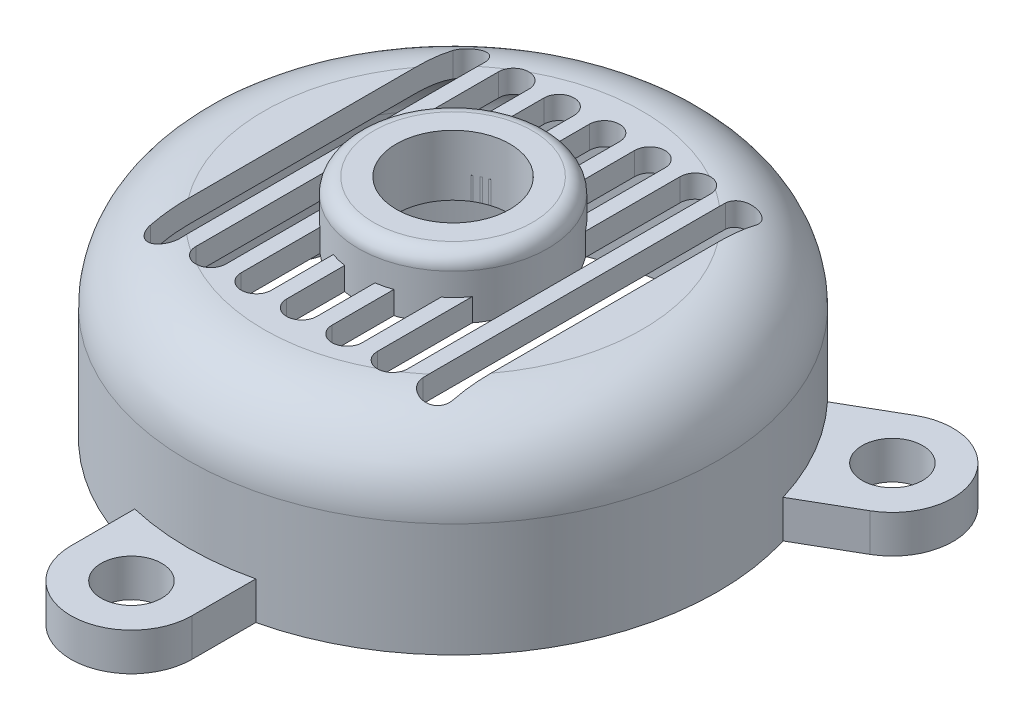
SolidWorks part; units mm, degrees
ref_plane "Front Plane" through (0, 0, 0) normal (0, 0, 1) x (1, 0, 0)
ref_plane "Top Plane" through (0, 0, 0) normal (0, 1, 0) x (1, 0, 0)
ref_plane "Right Plane" through (0, 0, 0) normal (1, 0, 0) x (0, 0, -1)
sketch "Sketch1" plane through (0, 0, 0) normal (0, 1, 0) x (1, 0, 0)
  circle A0 centre (0, 0) radius 35
  dimension "D1" = 35
extrude "Boss-Extrude1" add sketch "Sketch1" along normal blind 25
fillet "Fillet1" radius 10 1 edges at (0, 25, 35)
shell "Shell1" thickness 3
sketch "Sketch2" plane through (0, 0, 0) normal (0, -1, 0) x (1, 0, 0)
  line L1 (-8, 42.5) -> (8, 42.5) construction
  line L2 (-8, 42.5) -> (-8, 32)
  line L3 (-8, 32) -> (8, 32)
  line L4 (8, 42.5) -> (8, 32)
  line L5 (-8, 42.5) -> (8, 32) construction
  line L6 (-8, 32) -> (8, 42.5) construction
  arc A0 (8, 42.5) -> (-8, 42.5) centre (0, 42.5) ccw
  circle A1 centre (0, 42.5) radius 4
  circle A2 centre (0, 0) radius 32 construction
  point P0 (0, 37.25)
  point P8 (0, 0)
  dimension "D1" = 8
  dimension "D2" = 16
  dimension "D3" = 42.5
extrude "Boss-Extrude2" add sketch "Sketch2" against normal blind 5
pattern_circular "CirPattern1" count 3 over 360 about axis through (0, 0, 0) along (0, 1, 0) of "Boss-Extrude2"
sketch "Sketch3" plane through (0, 25, 0) normal (0, 1, 0) x (1, 0, 0)
  line L0 (-18, 20) -> (-18, -20) construction
  line L1 (-16, 20) -> (-16, -20)
  line L2 (-20, 20) -> (-20, -20)
  arc A0 (-16, 20) -> (-20, 20) centre (-18, 20) ccw
  arc A1 (-20, -20) -> (-16, -20) centre (-18, -20) ccw
  point P2 (-18, 0)
  point P7 (0, 0)
  dimension "D1" = 2
  dimension "D2" = 40
  dimension "D3" = 18
extrude "Cut-Extrude1" cut sketch "Sketch3" against normal through all
sketch "Sketch5" plane through (0, 25, 0) normal (0, 1, 0) x (1, 0, 0)
  line L0 (0, 0) -> (18.6501, 0)
pattern_linear "LPattern1" count 7 spacing 6 along (1, 0, 0) of "Cut-Extrude1"
sketch "Sketch6" plane through (0, 25, 0) normal (0, 1, 0) x (1, 0, 0)
  circle A0 centre (0, 0) radius 12.5
  dimension "D1" = 25
extrude "Boss-Extrude3" add sketch "Sketch6" along normal blind 5 and the other way blind 3 separate body
fillet "Fillet2" radius 2 1 edges at (0, 30, 12.5)
sketch "Sketch7" plane through (0, 30, 0) normal (0, 1, 0) x (1, 0, 0)
  circle A0 centre (0, 0) radius 7.5
  dimension "D1" = 15
extrude "Cut-Extrude2" cut sketch "Sketch7" against normal through all
